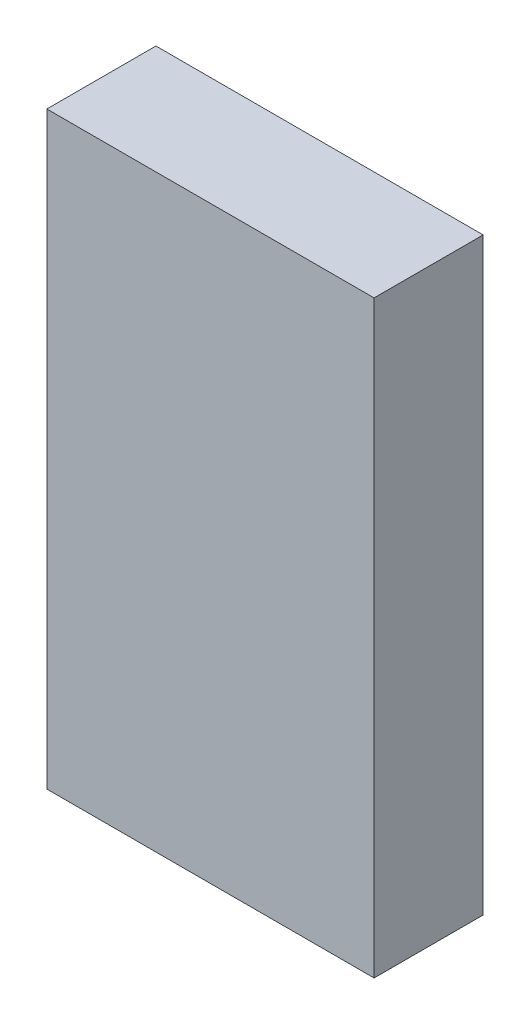
SolidWorks part; units mm, degrees
ref_plane "Front Plane" through (0, 0, 0) normal (0, 0, 1) x (1, 0, 0)
ref_plane "Top Plane" through (0, 0, 0) normal (0, 1, 0) x (1, 0, 0)
ref_plane "Right Plane" through (0, 0, 0) normal (1, 0, 0) x (0, 0, -1)
sketch "Sketch1" plane through (0, 0, 0) normal (0, 0, 1) x (1, 0, 0)
  line L1 (0, 0) -> (15, 0)
  line L2 (0, 0) -> (0, 27)
  line L3 (0, 27) -> (15, 27)
  line L4 (15, 0) -> (15, 27)
  dimension "D1" = 27
  dimension "D2" = 15
extrude "Boss-Extrude1" add sketch "Sketch1" along normal blind 5
